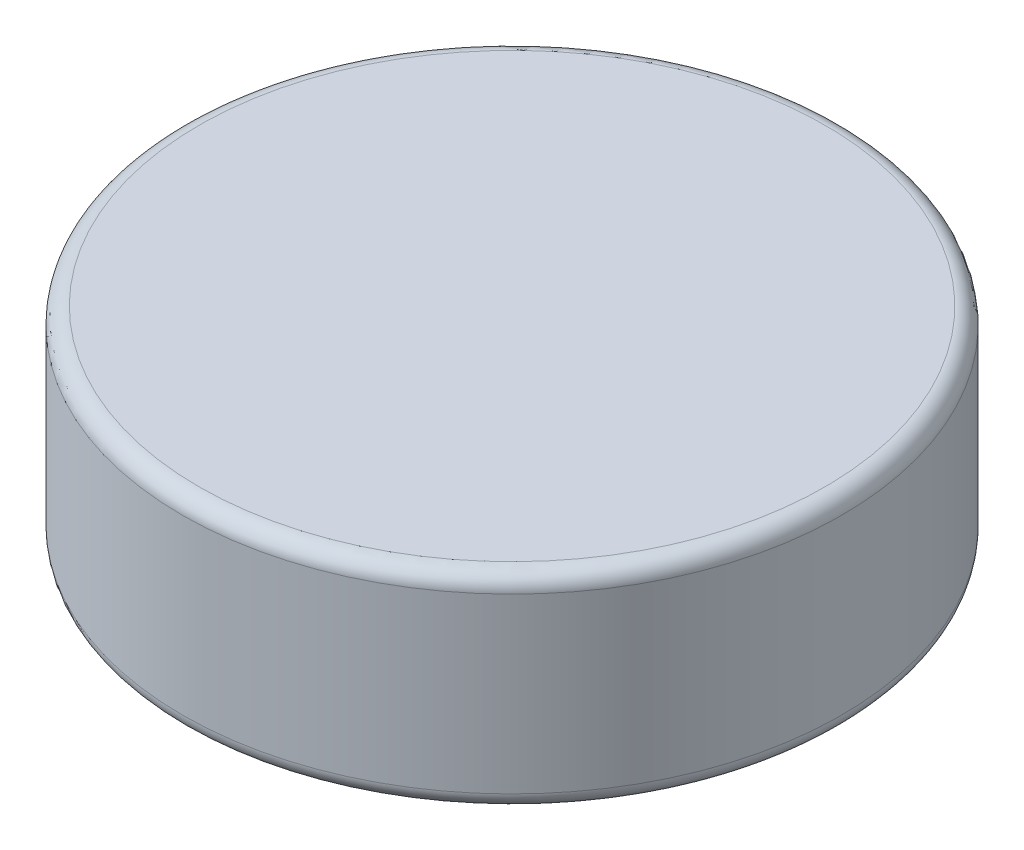
SolidWorks part; units mm, degrees
material "1060 Alloy"
ref_plane "Front Plane" through (0, 0, 0) normal (0, 0, 1) x (1, 0, 0)
ref_plane "Top Plane" through (0, 0, 0) normal (0, 1, 0) x (1, 0, 0)
ref_plane "Right Plane" through (0, 0, 0) normal (1, 0, 0) x (0, 0, -1)
sketch "Sketch1" plane through (0, 0, 0) normal (0, 1, 0) x (1, 0, 0)
  circle A0 centre (0, 0) radius 4
  dimension "D1" = 8
extrude "Boss-Extrude1" add sketch "Sketch1" along normal blind 2.5
fillet "Fillet1" radius 0.2 2 edges at (0, 0, 4) (0, 2.5, 4)
